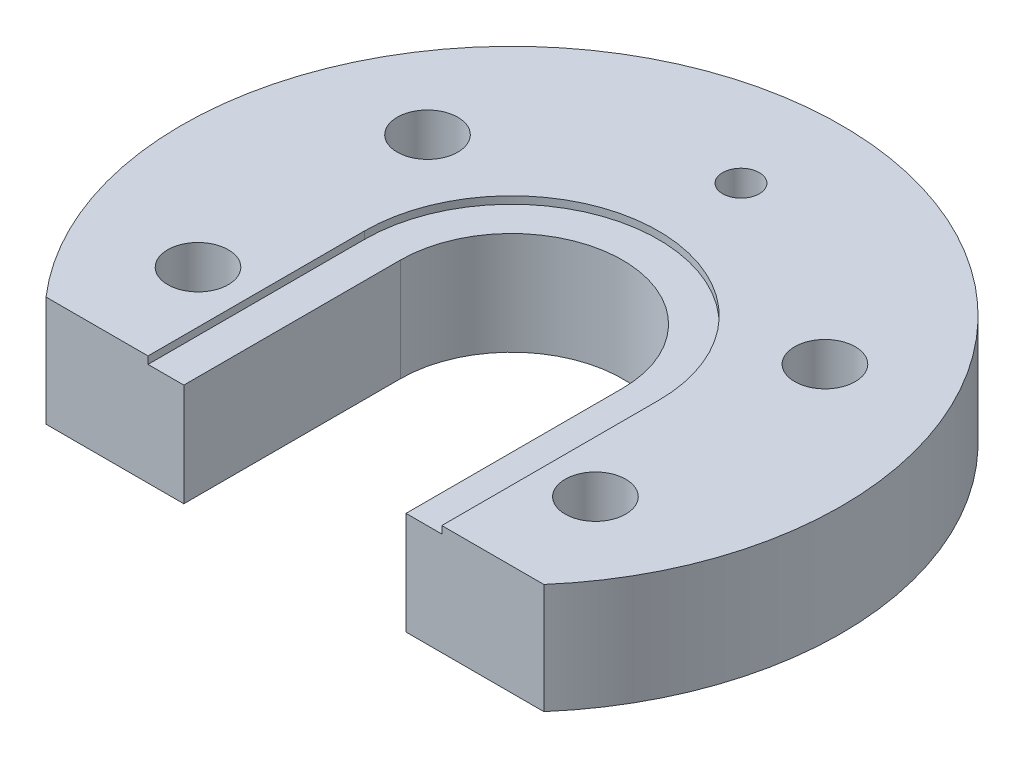
SolidWorks part; units mm, degrees
ref_plane "Front Plane" through (0, 0, 0) normal (0, 0, 1) x (1, 0, 0)
ref_plane "Top Plane" through (0, 0, 0) normal (0, 1, 0) x (1, 0, 0)
ref_plane "Right Plane" through (0, 0, 0) normal (1, 0, 0) x (0, 0, -1)
sketch "Sketch1" plane through (0, 0, 0) normal (0, 1, 0) x (1, 0, 0)
  line L0 (13.5562, -11.795) -> (6.05, -11.795)
  line L1 (-6.05, 0) -> (-6.05, -11.795)
  line L2 (6.05, 0) -> (6.05, -11.795)
  line L3 (-6.05, -11.795) -> (-13.5562, -11.795)
  arc A0 (13.5562, -11.795) -> (-13.5562, -11.795) centre (0, 0) ccw
  arc A1 (6.05, 0) -> (-6.05, 0) centre (0, 0) ccw
  circle A2 centre (-10.8229, 6.2496) radius 1.65
  circle A3 centre (10.823, 6.2496) radius 1.65
  circle A4 centre (10.823, -6.2496) radius 1.65
  circle A5 centre (-10.8229, -6.2496) radius 1.65
  circle A6 centre (0, 12.4985) radius 1
  dimension "D1" = 35.9383
  dimension "D2" = 12.1
  dimension "D5" = 3.3
  dimension "D6" = 2
  dimension "D3" = 21.6459
  dimension "D4" = 10.823
  dimension "D7" = 12.4985
  dimension "D8" = 12.4991
  dimension "D9" = 6.2496
  dimension "D10" = 11.795
extrude "Boss-Extrude1" add sketch "Sketch1" along normal blind 6
sketch "Sketch2" plane through (0, 6, 0) normal (0, 1, 0) x (1, 0, 0)
  line L0 (-8, 0) -> (-8, -11.795)
  line L1 (-13.5562, -11.795) -> (-6.05, -11.795) construction
  line L2 (-8, -11.795) -> (8, -11.795)
  line L3 (6.05, -11.795) -> (13.5562, -11.795) construction
  line L4 (8, -11.795) -> (8, 0)
  arc A0 (8, 0) -> (-8, 0) centre (0, 0) ccw
extrude "Cut-Extrude1" cut sketch "Sketch2" against normal blind 0.4
